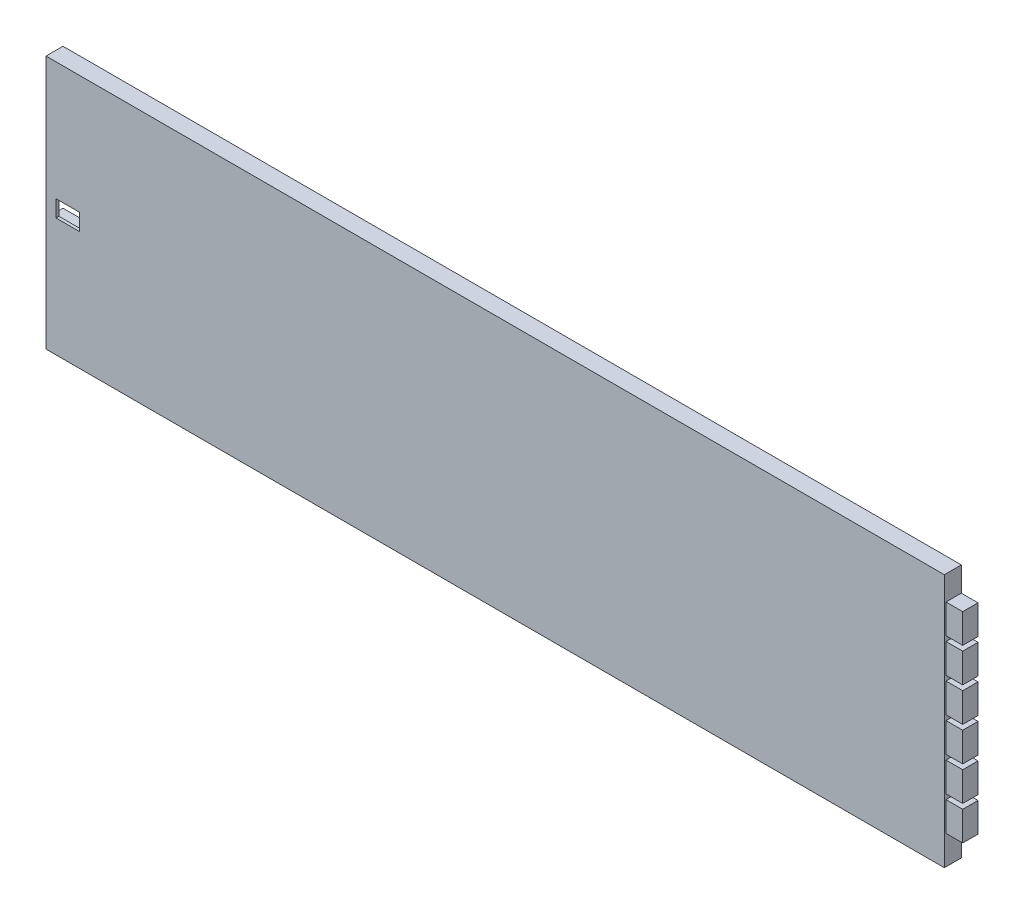
SolidWorks part; units mm, degrees
ref_plane "Front Plane" through (0, 0, 0) normal (0, 0, 1) x (1, 0, 0)
ref_plane "Top Plane" through (0, 0, 0) normal (0, 1, 0) x (1, 0, 0)
ref_plane "Right Plane" through (0, 0, 0) normal (1, 0, 0) x (0, 0, -1)
sketch "Sketch1" plane through (0, 0, 0) normal (1, 0, 0) x (0, 0, -1)
  line L1 (-2.54, 38) -> (2.54, 38)
  line L2 (-2.54, 38) -> (-2.54, -38)
  line L3 (-2.54, -38) -> (2.54, -38)
  line L4 (2.54, 38) -> (2.54, -38)
  line L5 (-2.54, 38) -> (2.54, -38) construction
  line L6 (-2.54, -38) -> (2.54, 38) construction
  point P0 (0, 0)
  dimension "D1" = 76
  dimension "D2" = 5.08
extrude "Boss-Extrude1" add sketch "Sketch1" along normal blind 269
sketch "Sketch2" plane through (269, 0, 0) normal (1, 0, 0) x (0, 0, -1)
  line L0 (2.54, -38) -> (2.54, 38) construction
  line L1 (2.54, 21.92) -> (-2.04, 21.92)
  line L2 (2.54, 21.92) -> (2.54, 30.67)
  line L3 (2.54, 30.67) -> (-2.04, 30.67)
  line L4 (-2.04, 21.92) -> (-2.04, 30.67)
  line L5 (2.54, 38) -> (-2.54, 38) construction
  line L6 (2.54, 1.42) -> (2.54, 10.17)
  line L7 (2.54, 11.67) -> (-2.04, 11.67)
  line L8 (2.54, 11.67) -> (2.54, 20.42)
  line L9 (2.54, 20.42) -> (-2.04, 20.42)
  line L10 (-2.04, 11.67) -> (-2.04, 20.42)
  line L11 (2.54, 1.42) -> (-2.04, 1.42)
  line L12 (-2.04, 1.42) -> (-2.04, 10.17)
  line L13 (2.54, 10.17) -> (-2.04, 10.17)
  line L14 (2.54, -8.83) -> (2.54, -0.08)
  line L15 (2.54, -8.83) -> (-2.04, -8.83)
  line L16 (-2.04, -8.83) -> (-2.04, -0.08)
  line L17 (2.54, -0.08) -> (-2.04, -0.08)
  line L18 (2.54, -19.08) -> (2.54, -10.33)
  line L19 (2.54, -19.08) -> (-2.04, -19.08)
  line L20 (-2.04, -19.08) -> (-2.04, -10.33)
  line L21 (2.54, -10.33) -> (-2.04, -10.33)
  line L22 (2.54, -29.33) -> (2.54, -20.58)
  line L23 (2.54, -29.33) -> (-2.04, -29.33)
  line L24 (-2.04, -29.33) -> (-2.04, -20.58)
  line L25 (2.54, -20.58) -> (-2.04, -20.58)
  line L26 (-2.54, 38) -> (-2.54, -38) construction
  dimension "D1" = 7.33
  dimension "D2" = 8.75
  dimension "D3" = 1.5
  dimension "D5" = 0.5
  dimension "D6" = 1.5
  dimension "D4" = 5
extrude "Boss-Extrude2" add sketch "Sketch2" along normal blind 5
sketch "Sketch5" plane through (0, 0, 0) normal (-1, 0, 0) x (0, 0, 1)
  line L0 (-2.54, -38) -> (-2.54, 38) construction
  line L1 (-2.54, -4) -> (1.66, -4)
  line L2 (-2.54, -4) -> (-2.54, 4)
  line L3 (-2.54, 4) -> (1.66, 4)
  line L4 (1.66, -4) -> (1.66, 4)
  line L5 (2.794, 0) -> (-2.794, 0) construction
  dimension "D1" = 4
  dimension "D2" = 4
  dimension "D3" = 4.2
extrude "Cut-Extrude1" cut sketch "Sketch5" against normal blind 15
sketch "Sketch6" plane through (0, 0, 1.66) normal (0, 0, -1) x (-1, 0, 0)
  line L0 (2.794, 0) -> (-2.794, 0) construction
  line L1 (-10, -2.5) -> (-3, -2.5)
  line L2 (-10, -2.5) -> (-10, 2.5)
  line L3 (-10, 2.5) -> (-3, 2.5)
  line L4 (-3, -2.5) -> (-3, 2.5)
  line L5 (-10, -2.5) -> (-3, 2.5) construction
  line L6 (-10, 2.5) -> (-3, -2.5) construction
  line L7 (-15, -4) -> (-15, 4) construction
  point P0 (-6.5, 0)
  dimension "D1" = 5
  dimension "D2" = 5
  dimension "D3" = 7
extrude "Cut-Extrude2" cut sketch "Sketch6" against normal blind 15
sketch "Sketch8" plane through (15, 0, 0) normal (-1, 0, 0) x (0, 0, 1)
  circle A0 centre (0, 0) radius 1.4
  dimension "D1" = 2.8
extrude "Boss-Extrude3" add sketch "Sketch8" along normal blind 2
